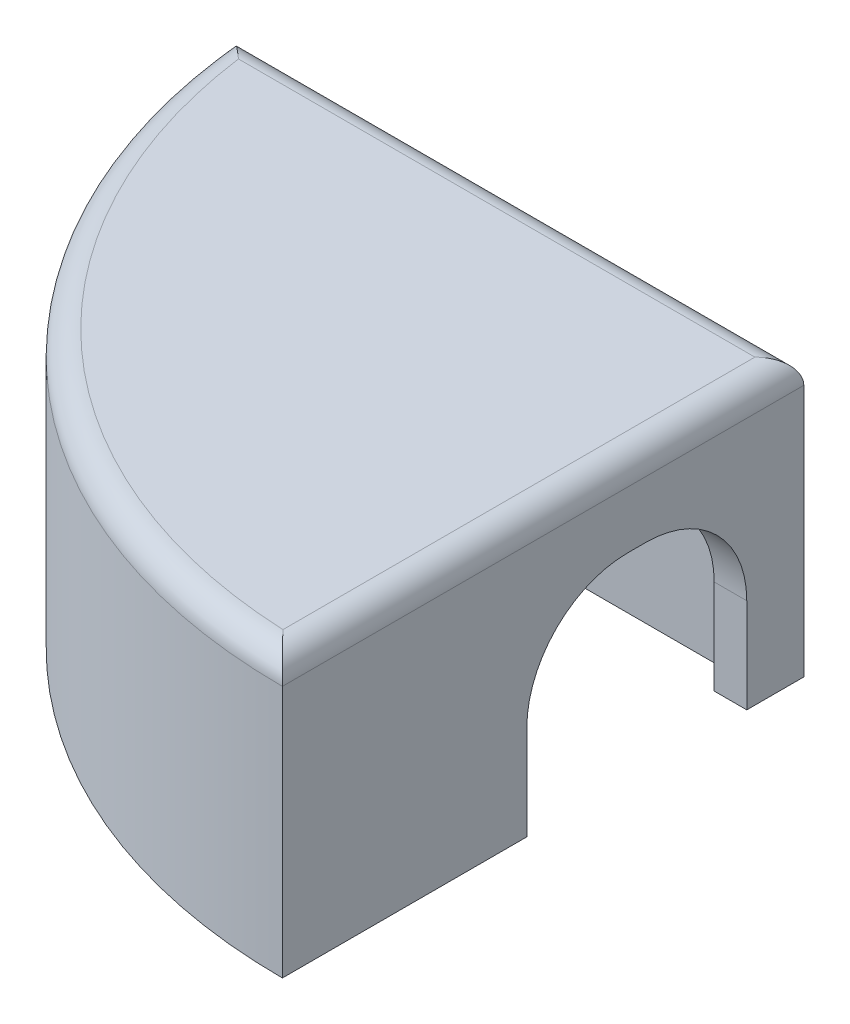
SolidWorks part; units mm, degrees
ref_plane "Front Plane" through (0, 0, 0) normal (0, 0, 1) x (1, 0, 0)
ref_plane "Top Plane" through (0, 0, 0) normal (0, 1, 0) x (1, 0, 0)
ref_plane "Right Plane" through (0, 0, 0) normal (1, 0, 0) x (0, 0, -1)
sketch "Sketch4" plane through (0, 0, 0) normal (0, 1, 0) x (1, 0, 0)
  line L3 (-60, -3) -> (-94.8712, -3)
  line L4 (-60, -35) -> (-60, -3)
  line L6 (-62, -5) -> (-93.1248, -5)
  line L7 (-62, -5) -> (-62, -33.4402)
  arc A1 (-94.8712, -3) -> (-60, -35) centre (-60, 0) ccw
  arc A3 (-93.1248, -5) -> (-62, -33.4402) centre (-60, 0) ccw
extrude "Boss-Extrude5" add sketch "Sketch4" along normal blind 15
sketch "Sketch5" plane through (0, 15, 0) normal (0, 1, 0) x (1, 0, 0)
  line L0 (-60, -3) -> (-94.8712, -3)
  line L1 (-60, -3) -> (-60, -35)
  arc A1 (-94.8712, -3) -> (-60, -35) centre (-60, 0) ccw
extrude "Boss-Extrude6" add sketch "Sketch5" along normal blind 2
fillet "Fillet2" radius 1.5 3 edges at (-83.6643, 17, 25.7876) (-77.4356, 17, 3) (-60, 17, 19)
sketch "Sketch7" plane through (-60, 0, 0) normal (1, 0, 0) x (0, 0, -1)
  line L0 (-3, 0) -> (-6.5, 0)
  line L1 (-35, 0) -> (-3, 0) construction
  line L2 (-6.5, 0) -> (-6.5, 12)
  line L3 (-6.5, 12) -> (-20, 12)
  line L4 (-20, 12) -> (-20, 0)
  line L5 (-6.5, 0) -> (-20, 0)
  line M8 (-35, 0) -> (-3, 0)
  dimension "D1" = 13.5
  dimension "D2" = 3.5
extrude "Cut-Extrude2" cut sketch "Sketch7" against normal blind 5 contours L3 L4 L2 M8
fillet "Fillet3" radius 6.2 2 edges at (-61, 12, 20) (-61, 12, 6.5)
